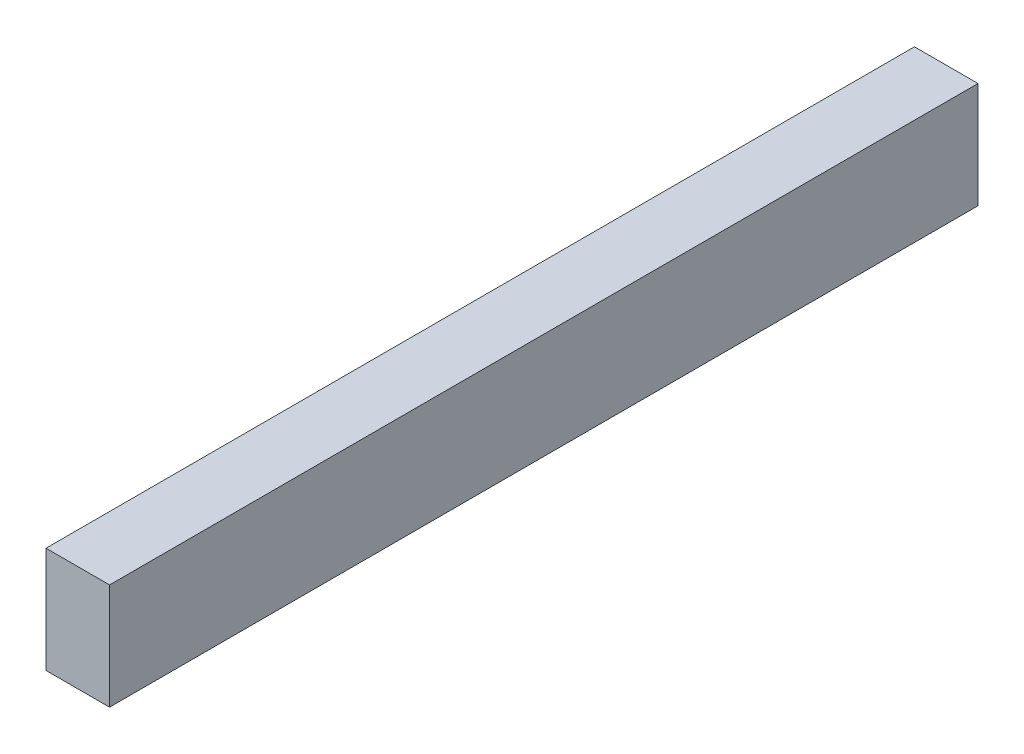
SolidWorks part; units mm, degrees
ref_plane "Front" through (0, 0, 0) normal (0, 0, 1) x (1, 0, 0)
ref_plane "Top" through (0, 0, 0) normal (0, 1, 0) x (1, 0, 0)
ref_plane "Right" through (0, 0, 0) normal (1, 0, 0) x (0, 0, -1)
sketch "Esquisse1" plane through (0, 0, 0) normal (0, 0, 1) x (1, 0, 0)
  line L1 (0, 0) -> (30, 0)
  line L2 (0, 0) -> (0, 50)
  line L3 (0, 50) -> (30, 50)
  line L4 (30, 0) -> (30, 50)
  dimension "D1" = 50
  dimension "D2" = 30
extrude "Boss.-Extru.1" add sketch "Esquisse1" along normal blind 410
